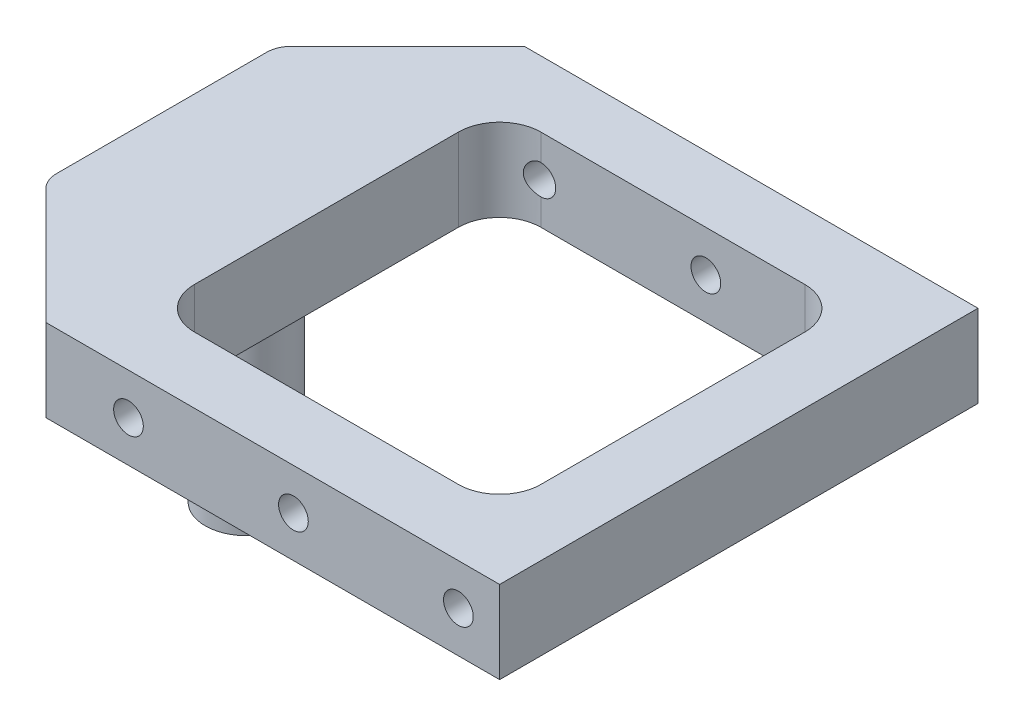
SolidWorks part; units mm, degrees
material "AISI 304"
ref_plane "Front Plane" through (0, 0, 0) normal (0, 0, 1) x (1, 0, 0)
ref_plane "Top Plane" through (0, 0, 0) normal (0, 1, 0) x (1, 0, 0)
ref_plane "Right Plane" through (0, 0, 0) normal (1, 0, 0) x (0, 0, -1)
sketch "Sketch1" plane through (0, 0, -7.1063) normal (0, 0, 1) x (1, 0, 0)
  line L1 (24.9678, -105) -> (-45.0322, -105)
  line L2 (24.9678, -105) -> (24.9678, -95)
  line L3 (24.9678, -95) -> (-45.0322, -95)
  line L4 (-45.0322, -105) -> (-45.0322, -95)
  dimension "D1" = 10
  dimension "D2" = 70
extrude "Extrude1" add sketch "Sketch1" along normal blind 58
sketch "Sketch2" plane through (0, -105, 0) normal (0, -1, 0) x (1, 0, 0)
  line L0 (27.6368, 36.5937) -> (27.6368, 6.5937) construction
  line L1 (38.7, 36.5937) -> (-38.7, 36.5937) construction
  line L2 (-38.7, 6.5937) -> (38.7, 6.5937) construction
  line L3 (27.6368, 21.5937) -> (-35.0322, 21.5937) construction
  line L4 (-45.0322, 50.8937) -> (-45.0322, -7.1063) construction
  circle A0 centre (-35.0322, 21.5937) radius 5
  dimension "D2" = 10
  dimension "D1" = 10
extrude "Extrude2" add sketch "Sketch2" along normal blind 26
sketch "Sketch3" plane through (0, -105, 0) normal (0, -1, 0) x (1, 0, 0)
  line L0 (-45.0322, 50.8937) -> (24.9678, 50.8937) construction
  line L1 (-20.0322, 42.8937) -> (11.9678, 42.8937)
  line L2 (-25.0322, 37.8937) -> (-25.0322, 5.8937)
  line L3 (-20.0322, 0.8937) -> (11.9678, 0.8937)
  line L4 (16.9678, 37.8937) -> (16.9678, 5.8937)
  line L5 (-45.0322, -7.1063) -> (24.9678, -7.1063) construction
  line L6 (24.9678, 50.8937) -> (24.9678, -7.1063) construction
  line L7 (-45.0322, 50.8937) -> (-45.0322, -7.1063) construction
  arc A0 (-25.0322, 5.8937) -> (-20.0322, 0.8937) centre (-20.0322, 5.8937) ccw
  arc A1 (11.9678, 0.8937) -> (16.9678, 5.8937) centre (11.9678, 5.8937) ccw
  arc A2 (11.9678, 42.8937) -> (16.9678, 37.8937) centre (11.9678, 37.8937) cw
  arc A3 (-20.0322, 42.8937) -> (-25.0322, 37.8937) centre (-20.0322, 37.8937) ccw
  dimension "D5" = 5
  dimension "D1" = 8
  dimension "D2" = 8
  dimension "D3" = 8
  dimension "D4" = 20
extrude "Cut-Extrude1" cut sketch "Sketch3" against normal blind 30
chamfer "Chamfer1" distance 15 angle 45 2 edges at (-45.0322, -100, -7.1063) (-45.0322, -100, 50.8937)
fillet "Fillet1" radius 3 2 edges at (-45.0322, -100, 7.8937) (-45.0322, -100, 35.8937)
sketch "Sketch4" plane through (0, 0, 50.8937) normal (0, 0, 1) x (1, 0, 0)
  line L0 (-20.0322, -95) -> (-20.0322, -105) construction
  circle A0 centre (-20.0322, -100) radius 1.8
  circle A1 centre (-0.0322, -100) radius 1.8
  circle A2 centre (19.9678, -100) radius 1.8
  dimension "D1" = 3.6
extrude "Cut-Extrude2" cut sketch "Sketch4" against normal blind 60
